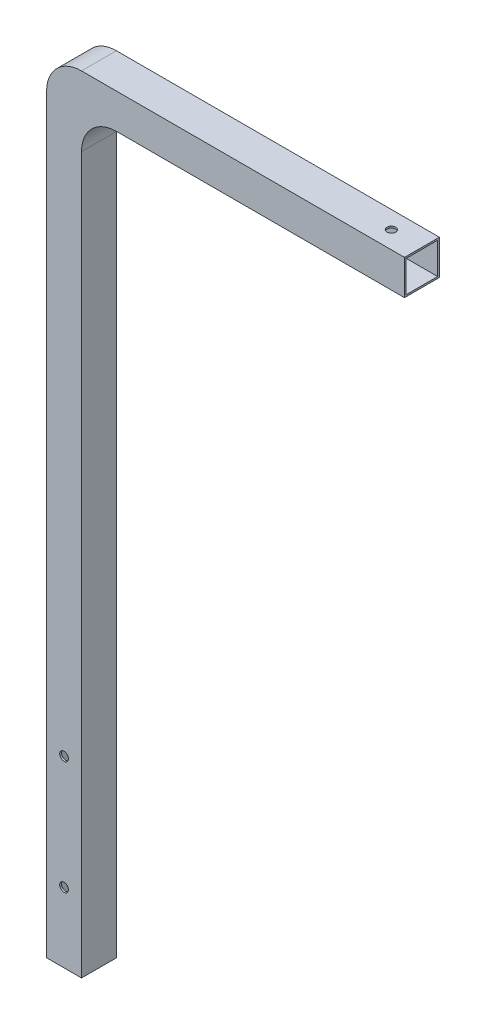
SolidWorks part; units mm, degrees
material "Alloy Steel"
ref_plane "Front Plane" through (0, 0, 0) normal (0, 0, 1) x (1, 0, 0)
ref_plane "Top Plane" through (0, 0, 0) normal (0, 1, 0) x (1, 0, 0)
ref_plane "Right Plane" through (0, 0, 0) normal (1, 0, 0) x (0, 0, -1)
sketch "Sketch1" plane through (0, 0, 0) normal (0, 0, 1) x (1, 0, 0)
  line L0 (0, 0) -> (0, 1143)
  line L1 (0, 1143) -> (520.7, 1143)
  line L2 (50.8, 0) -> (50.8, 1092.2)
  line L3 (50.8, 1092.2) -> (520.7, 1092.2)
  line L4 (520.7, 1143) -> (520.7, 1092.2)
  line L5 (0, 0) -> (50.8, 0)
  dimension "D1" = 1143
  dimension "D2" = 520.7
  dimension "D3" = 50.8
extrude "Boss-Extrude1" add sketch "Sketch1" along normal blind 50.8
fillet "Fillet1" radius 50.8 2 edges at (50.8, 1092.2, 25.4) (0, 1143, 25.4)
shell "Shell1" thickness 2.54
sketch "Sketch2" plane through (0, 0, 0) normal (0, -1, 0) x (1, 0, 0)
  line L0 (48.26, 48.26) -> (2.54, 48.26)
  line L1 (2.54, 48.26) -> (2.54, 2.54)
  line L2 (2.54, 2.54) -> (48.26, 2.54)
  line L3 (48.26, 2.54) -> (48.26, 48.26)
extrude "Cut-Extrude1" cut sketch "Sketch2" against normal blind 50.8
hole_wizard "#97 (0.5) Diameter Hole1" positions "3DSketch1" profile "Sketch3" hole size "#97" standard "ANSI Inch" end condition through all
sketch3d "3DSketch1"
  line L0 (520.7, 1143, 0) -> (50.8, 1143, 0) construction
  line L1 (520.7, 1143, 50.8) -> (520.7, 1143, 0) construction
  point P0 (476.25, 1143, 25.4)
  dimension "D1" = 25.4
  dimension "D2" = 44.45
sketch "Sketch3" plane through (476.25, 1143, 25.4) normal (1, 0, 0) x (0, 0, 1)
  line L0 (0, 0) -> (0, 1143)
  line L1 (0, 1143) -> (6.35, 1143)
  line L2 (6.35, 1143) -> (6.35, 0)
  line L5 (6.35, 0) -> (0, 0)
  line L11 (0, -6.35) -> (0, 107.95) construction
  dimension "Thru Hole Dia." = 12.7
  dimension "Thru Hole Depth" = 1143
hole_wizard "#97 (0.5) Diameter Hole2" positions "3DSketch2" profile "Sketch4" hole size "#97" standard "ANSI Inch" end condition through all
sketch3d "3DSketch2"
  line L0 (0, 1092.2, 50.8) -> (0, 0, 50.8) construction
  line L1 (0, 0, 50.8) -> (50.8, 0, 50.8) construction
  point P0 (25.4, 101.6, 50.8)
  point P2 (25.4, 266.7, 50.8)
  dimension "D1" = 25.4
  dimension "D2" = 25.4
  dimension "D3" = 101.6
  dimension "D4" = 165.1
sketch "Sketch4" plane through (25.4, 101.6, 50.8) normal (1, 0, 0) x (0, -1, 0)
  line L0 (0, 0) -> (0, 50.8)
  line L1 (0, 50.8) -> (6.35, 50.8)
  line L2 (6.35, 50.8) -> (6.35, 0)
  line L5 (6.35, 0) -> (0, 0)
  line L11 (0, -6.35) -> (0, 107.95) construction
  dimension "Thru Hole Dia." = 12.7
  dimension "Thru Hole Depth" = 50.8
